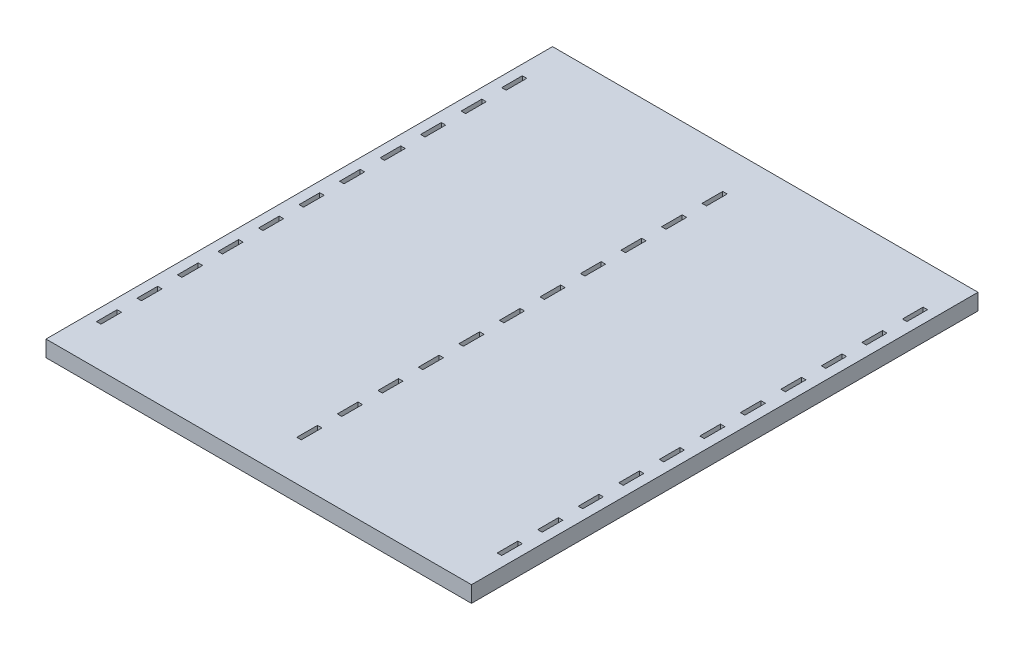
SolidWorks part; units mm, degrees
other "标注1"
sketch "草图3"
ref_plane "Front Plane" through (0, 0, 0) normal (0, 0, 1) x (1, 0, 0)
ref_plane "Top Plane" through (0, 0, 0) normal (0, 1, 0) x (1, 0, 0)
ref_plane "Right Plane" through (0, 0, 0) normal (1, 0, 0) x (0, 0, -1)
sketch "Sketch1" plane through (0, 0, 0) normal (0, 1, 0) x (1, 0, 0)
  line L1 (105, -125) -> (-105, -125)
  line L2 (105, -125) -> (105, 125)
  line L3 (105, 125) -> (-105, 125)
  line L4 (-105, -125) -> (-105, 125)
  line L5 (105, -125) -> (-105, 125) construction
  line L6 (105, 125) -> (-105, -125) construction
  point P0 (0, 0)
  dimension "D1" = 210
  dimension "D2" = 250
extrude "Boss-Extrude1" add sketch "Sketch1" along normal blind 8
sketch "草图2" plane through (0, 8, 0) normal (0, 1, 0) x (1, 0, 0)
  line L0 (1.1, -14.9) -> (1.1, -25.1)
  line L1 (1.1, 5.1) -> (-1.1, 5.1)
  line L2 (1.1, 5.1) -> (1.1, -5.1)
  line L3 (1.1, -5.1) -> (-1.1, -5.1)
  line L4 (-1.1, 5.1) -> (-1.1, -5.1)
  line L5 (1.1, 5.1) -> (-1.1, -5.1) construction
  line L6 (1.1, -5.1) -> (-1.1, 5.1) construction
  line L7 (1.1, 25.1) -> (1.1, 14.9)
  line L8 (1.1, -14.9) -> (-1.1, -14.9)
  line L9 (1.1, 25.1) -> (-1.1, 25.1)
  line L10 (-1.1, 25.1) -> (-1.1, 14.9)
  line L11 (1.1, 14.9) -> (-1.1, 14.9)
  line L12 (1.1, 45.1) -> (1.1, 34.9)
  line L13 (1.1, 45.1) -> (-1.1, 45.1)
  line L14 (-1.1, 45.1) -> (-1.1, 34.9)
  line L15 (1.1, 34.9) -> (-1.1, 34.9)
  line L16 (1.1, 65.1) -> (1.1, 54.9)
  line L17 (1.1, 65.1) -> (-1.1, 65.1)
  line L18 (-1.1, 65.1) -> (-1.1, 54.9)
  line L19 (1.1, 54.9) -> (-1.1, 54.9)
  line L20 (1.1, 85.1) -> (1.1, 74.9)
  line L21 (1.1, 85.1) -> (-1.1, 85.1)
  line L22 (-1.1, 85.1) -> (-1.1, 74.9)
  line L23 (1.1, 74.9) -> (-1.1, 74.9)
  line L24 (1.1, 105.1) -> (1.1, 94.9)
  line L25 (1.1, 105.1) -> (-1.1, 105.1)
  line L26 (-1.1, 105.1) -> (-1.1, 94.9)
  line L27 (1.1, 94.9) -> (-1.1, 94.9)
  line L28 (-1.1, -14.9) -> (-1.1, -25.1)
  line L29 (1.1, -25.1) -> (-1.1, -25.1)
  line L30 (1.1, -34.9) -> (1.1, -45.1)
  line L31 (1.1, -34.9) -> (-1.1, -34.9)
  line L32 (-1.1, -34.9) -> (-1.1, -45.1)
  line L33 (1.1, -45.1) -> (-1.1, -45.1)
  line L34 (1.1, -54.9) -> (1.1, -65.1)
  line L35 (1.1, -54.9) -> (-1.1, -54.9)
  line L36 (-1.1, -54.9) -> (-1.1, -65.1)
  line L37 (1.1, -65.1) -> (-1.1, -65.1)
  line L38 (1.1, -74.9) -> (1.1, -85.1)
  line L39 (1.1, -74.9) -> (-1.1, -74.9)
  line L40 (-1.1, -74.9) -> (-1.1, -85.1)
  line L41 (1.1, -85.1) -> (-1.1, -85.1)
  line L42 (1.1, -94.9) -> (1.1, -105.1)
  line L43 (1.1, -94.9) -> (-1.1, -94.9)
  line L44 (-1.1, -94.9) -> (-1.1, -105.1)
  line L45 (1.1, -105.1) -> (-1.1, -105.1)
  line L46 (97.8, -5.1) -> (100, -5.1)
  line L47 (100, 5.1) -> (100, -5.1)
  line L48 (97.8, 5.1) -> (100, 5.1)
  line L49 (97.8, 5.1) -> (97.8, -5.1)
  line L50 (97.8, 14.9) -> (100, 14.9)
  line L51 (-97.8, 5.1) -> (-97.8, -5.1)
  line L52 (-97.8, 5.1) -> (-100, 5.1)
  line L53 (-100, 5.1) -> (-100, -5.1)
  line L54 (-97.8, -5.1) -> (-100, -5.1)
  line L55 (100, 25.1) -> (100, 14.9)
  line L56 (97.8, 25.1) -> (100, 25.1)
  line L57 (97.8, 25.1) -> (97.8, 14.9)
  line L58 (97.8, 34.9) -> (100, 34.9)
  line L59 (100, 45.1) -> (100, 34.9)
  line L60 (97.8, 45.1) -> (100, 45.1)
  line L61 (97.8, 45.1) -> (97.8, 34.9)
  line L62 (97.8, 54.9) -> (100, 54.9)
  line L63 (100, 65.1) -> (100, 54.9)
  line L64 (97.8, 65.1) -> (100, 65.1)
  line L65 (97.8, 65.1) -> (97.8, 54.9)
  line L66 (97.8, 74.9) -> (100, 74.9)
  line L67 (100, 85.1) -> (100, 74.9)
  line L68 (97.8, 85.1) -> (100, 85.1)
  line L69 (97.8, 85.1) -> (97.8, 74.9)
  line L70 (97.8, 94.9) -> (100, 94.9)
  line L71 (100, 105.1) -> (100, 94.9)
  line L72 (97.8, 105.1) -> (100, 105.1)
  line L73 (97.8, 105.1) -> (97.8, 94.9)
  line L74 (97.8, -5.1) -> (97.8, 14.9) construction
  line L75 (97.8, -25.1) -> (100, -25.1)
  line L76 (100, -14.9) -> (100, -25.1)
  line L77 (97.8, -14.9) -> (100, -14.9)
  line L78 (97.8, -14.9) -> (97.8, -25.1)
  line L79 (97.8, -45.1) -> (100, -45.1)
  line L80 (100, -34.9) -> (100, -45.1)
  line L81 (97.8, -34.9) -> (100, -34.9)
  line L82 (97.8, -34.9) -> (97.8, -45.1)
  line L83 (97.8, -65.1) -> (100, -65.1)
  line L84 (100, -54.9) -> (100, -65.1)
  line L85 (97.8, -54.9) -> (100, -54.9)
  line L86 (97.8, -54.9) -> (97.8, -65.1)
  line L87 (97.8, -85.1) -> (100, -85.1)
  line L88 (100, -74.9) -> (100, -85.1)
  line L89 (97.8, -74.9) -> (100, -74.9)
  line L90 (97.8, -74.9) -> (97.8, -85.1)
  line L91 (97.8, -105.1) -> (100, -105.1)
  line L92 (100, -94.9) -> (100, -105.1)
  line L93 (97.8, -94.9) -> (100, -94.9)
  line L94 (97.8, -94.9) -> (97.8, -105.1)
  line L95 (-100, 25.1) -> (-100, 14.9)
  line L96 (-97.8, 25.1) -> (-97.8, 14.9)
  line L97 (-97.8, 14.9) -> (-100, 14.9)
  line L98 (-97.8, 25.1) -> (-100, 25.1)
  line L99 (-100, 45.1) -> (-100, 34.9)
  line L100 (-97.8, 45.1) -> (-97.8, 34.9)
  line L101 (-97.8, 34.9) -> (-100, 34.9)
  line L102 (-97.8, 45.1) -> (-100, 45.1)
  line L103 (-100, 65.1) -> (-100, 54.9)
  line L104 (-97.8, 65.1) -> (-97.8, 54.9)
  line L105 (-97.8, 54.9) -> (-100, 54.9)
  line L106 (-97.8, 65.1) -> (-100, 65.1)
  line L107 (-100, 85.1) -> (-100, 74.9)
  line L108 (-97.8, 85.1) -> (-97.8, 74.9)
  line L109 (-97.8, 74.9) -> (-100, 74.9)
  line L110 (-97.8, 85.1) -> (-100, 85.1)
  line L111 (-100, 105.1) -> (-100, 94.9)
  line L112 (-97.8, 105.1) -> (-97.8, 94.9)
  line L113 (-97.8, 94.9) -> (-100, 94.9)
  line L114 (-97.8, 105.1) -> (-100, 105.1)
  line L115 (-97.8, -14.9) -> (-97.8, -25.1)
  line L116 (-97.8, -25.1) -> (-100, -25.1)
  line L117 (-100, -14.9) -> (-100, -25.1)
  line L118 (-97.8, -14.9) -> (-100, -14.9)
  line L119 (-97.8, -34.9) -> (-97.8, -45.1)
  line L120 (-97.8, -45.1) -> (-100, -45.1)
  line L121 (-100, -34.9) -> (-100, -45.1)
  line L122 (-97.8, -34.9) -> (-100, -34.9)
  line L123 (-97.8, -54.9) -> (-97.8, -65.1)
  line L124 (-97.8, -65.1) -> (-100, -65.1)
  line L125 (-100, -54.9) -> (-100, -65.1)
  line L126 (-97.8, -54.9) -> (-100, -54.9)
  line L127 (-97.8, -74.9) -> (-97.8, -85.1)
  line L128 (-97.8, -85.1) -> (-100, -85.1)
  line L129 (-100, -74.9) -> (-100, -85.1)
  line L130 (-97.8, -74.9) -> (-100, -74.9)
  line L131 (-97.8, -94.9) -> (-97.8, -105.1)
  line L132 (-97.8, -105.1) -> (-100, -105.1)
  line L133 (-100, -94.9) -> (-100, -105.1)
  line L134 (-97.8, -94.9) -> (-100, -94.9)
  point P0 (0, 0)
  dimension "D1" = 6
  dimension "D2" = 2.2
  dimension "D3" = 6
  dimension "D5" = 6
  dimension "D4" = 6
  dimension "D6" = 6
  dimension "D7" = 6
extrude "切除-拉伸3" cut sketch "草图2" against normal through all
